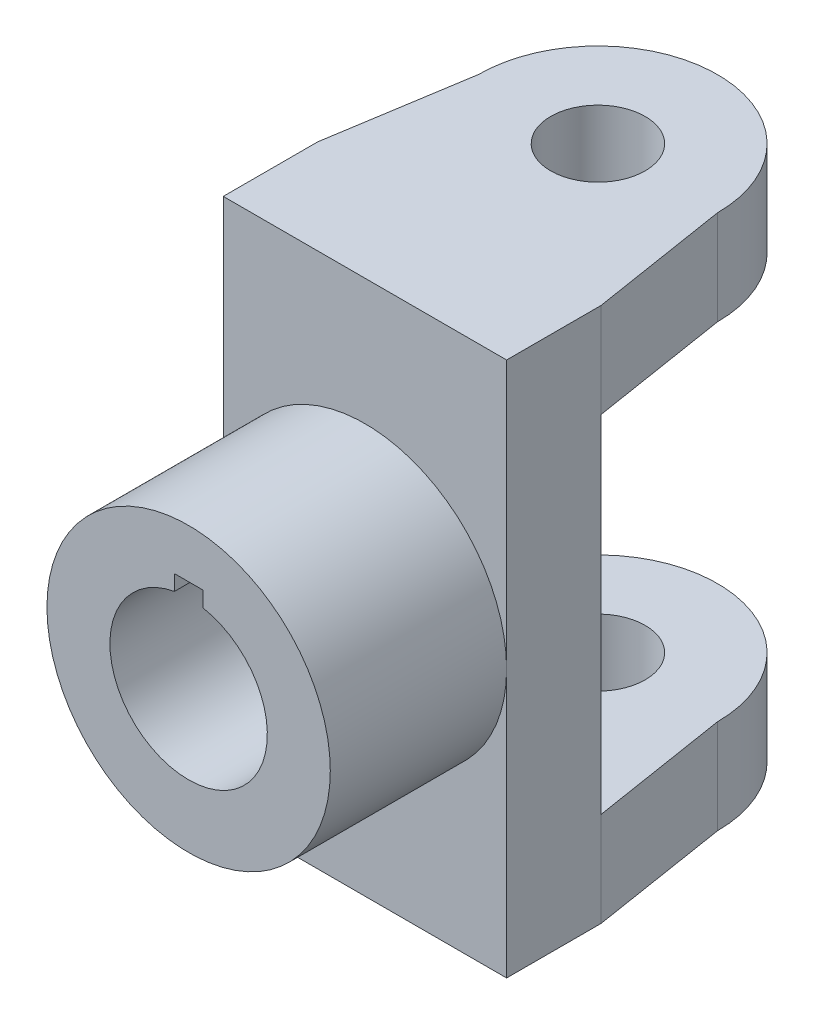
SolidWorks part; units mm, degrees
ref_plane "Front Plane" through (0, 0, 0) normal (0, 0, 1) x (1, 0, 0)
ref_plane "Top Plane" through (0, 0, 0) normal (0, 1, 0) x (1, 0, 0)
ref_plane "Right Plane" through (0, 0, 0) normal (1, 0, 0) x (0, 0, -1)
sketch "Sketch2" plane through (0, 0, 0) normal (0, 0, 1) x (1, 0, 0)
  line L4 (-4.5, 29.4917) -> (4.5, 29.4917)
  line L5 (-4.5, 29.4917) -> (-4.5, 24.5917)
  line L7 (4.5, 29.4917) -> (4.5, 24.5917)
  circle A0 centre (0, 0) radius 45
  arc A1 (-4.5, 24.5917) -> (4.5, 24.5917) centre (0, 0) ccw
  dimension "D1" = 50
  dimension "D2" = 90
  dimension "D3" = 9
  dimension "D4" = 4.9
extrude "Boss-Extrude3" add sketch "Sketch2" against normal blind 56 contours L5 A1 L7 L4 | A0
sketch "Sketch4" plane through (0, 0, -56) normal (0, 0, -1) x (-1, 0, 0)
  line L0 (0, 57.9712) -> (0, -56.6178) construction
  line L1 (-66.5429, 0) -> (63.1593, 0) construction
  line L3 (-45, 85) -> (45, 85)
  line L4 (-45, 85) -> (-45, -85)
  line L5 (-45, -85) -> (45, -85)
  line L6 (45, 85) -> (45, -85)
  line L7 (-45, 85) -> (45, -85) construction
  line L8 (-45, -85) -> (45, 85) construction
  point P5 (0, 0)
extrude "Boss-Extrude4" add sketch "Sketch4" along normal blind 30
sketch "Sketch6" plane through (0, 85, 0) normal (0, 1, 0) x (1, 0, 0)
  line L0 (0, 86) -> (0, -35.6304) construction
  line L1 (-84.5794, 86) -> (52.7651, 86) construction
  line L3 (-45, 86) -> (-38, 130)
  line L4 (45, 86) -> (38, 130)
  arc A0 (38, 130) -> (-38, 130) centre (0, 130) ccw
  circle A1 centre (0, 130) radius 15
  line M6 (45, 86) -> (-45, 86)
extrude "Boss-Extrude5" add sketch "Sketch6" against normal blind 170 contours L4 A0 L3 A1 M6
sketch "Sketch11" plane through (0, 0, 0) normal (1, 0, 0) x (0, 0, -1)
  line L0 (0, 0) -> (232.929, 0) construction
  line L1 (86, 85) -> (86, -85) construction
  line L2 (86, -55) -> (218.3813, -55)
  line L3 (86, -55) -> (86, 55)
  line L4 (86, 55) -> (218.3813, 55)
  line L5 (218.3813, -55) -> (218.3813, 55)
  line L6 (86, 85) -> (130, 85) construction
  line L7 (86, -85) -> (130, -85) construction
  dimension "D1" = 30
  dimension "D2" = 30
extrude "Cut-Extrude3" cut sketch "Sketch11" against normal mid plane 260
